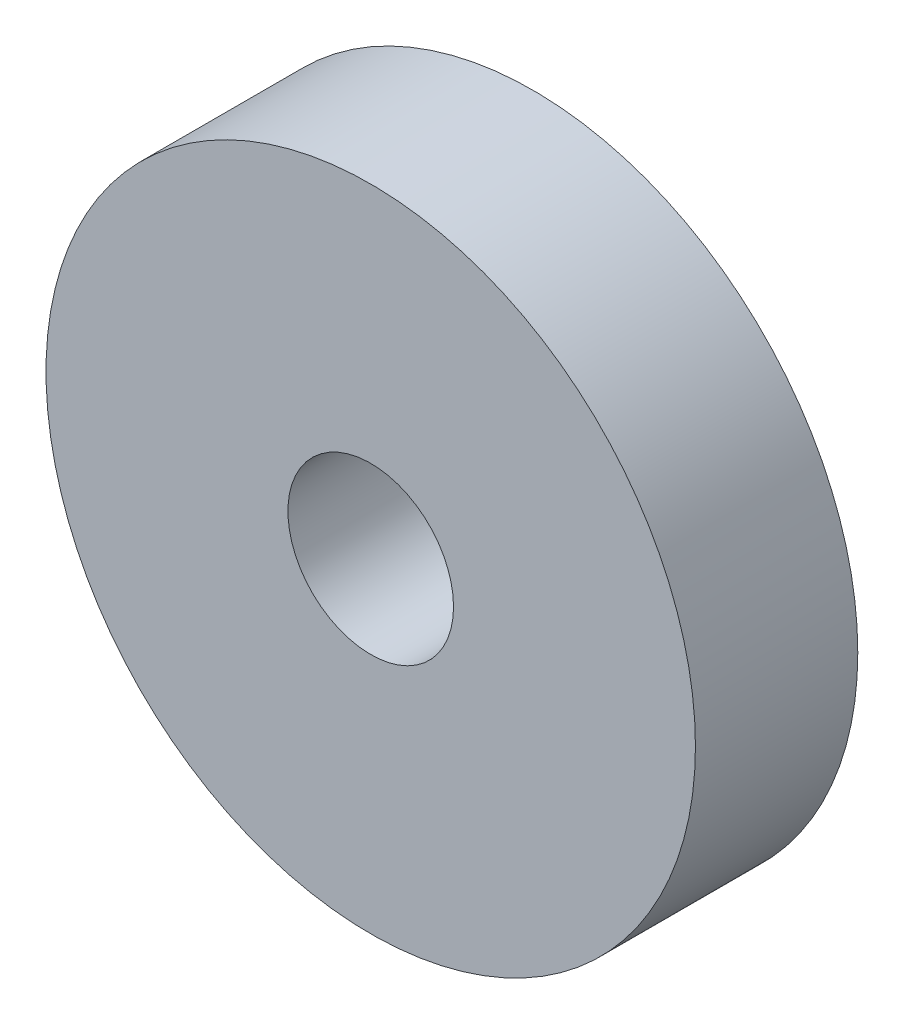
SolidWorks part; units mm, degrees
ref_plane "Front Plane" through (0, 0, 0) normal (0, 0, 1) x (1, 0, 0)
ref_plane "Top Plane" through (0, 0, 0) normal (0, 1, 0) x (1, 0, 0)
ref_plane "Right Plane" through (0, 0, 0) normal (1, 0, 0) x (0, 0, -1)
sketch "Sketch1" plane through (0, 0, 0) normal (0, 0, 1) x (1, 0, 0)
  circle A0 centre (0, 0) radius 10
  circle A1 centre (0, 0) radius 2.55
  dimension "D1" = 20
  dimension "D2" = 5.1
extrude "Boss-Extrude1" add sketch "Sketch1" along normal blind 5
